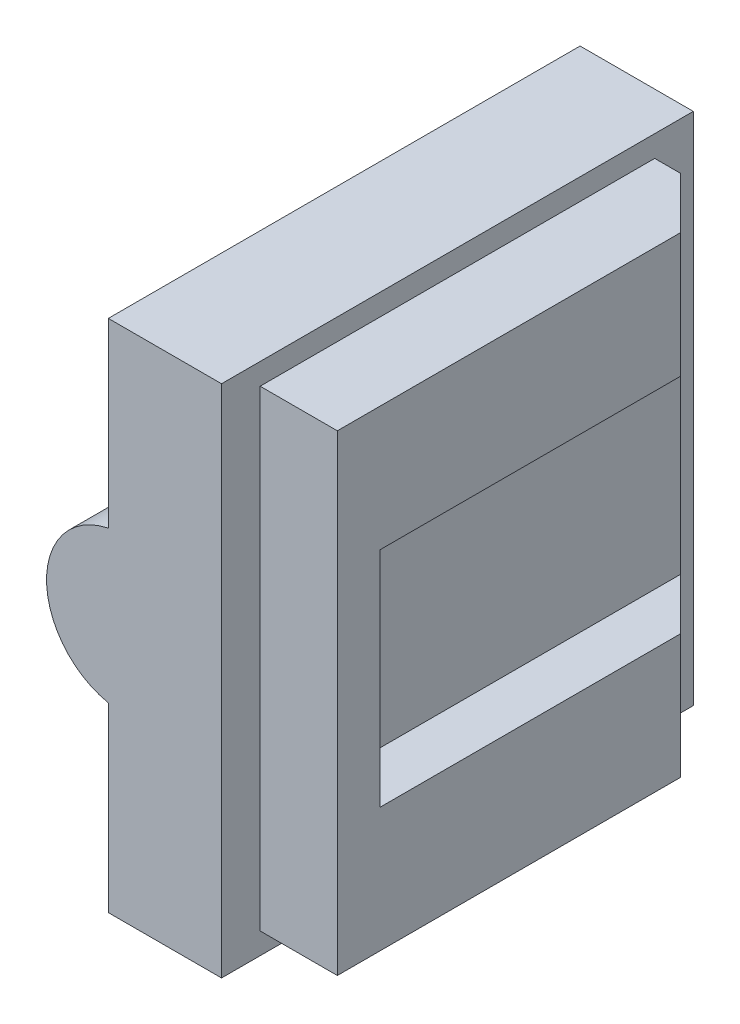
SolidWorks part; units mm, degrees
ref_plane "前视基准面" through (0, 0, 0) normal (0, 0, 1) x (1, 0, 0)
ref_plane "上视基准面" through (0, 0, 0) normal (0, 1, 0) x (1, 0, 0)
ref_plane "右视基准面" through (0, 0, 0) normal (1, 0, 0) x (0, 0, -1)
other "Configuration Table"
sketch "草图1" plane through (0, 0, 0) normal (0, 1, 0) x (1, 0, 0)
  line L0 (-0.3058, 8.6946) -> (9.8, 9.05)
  line L1 (9.8, 9.05) -> (9.8, -9.05)
  line L2 (9.8, -9.05) -> (-0.3058, -8.6946)
  line L3 (0, 0) -> (9.8, 0) construction
  circle A0 centre (0, 0) radius 2.9
  arc A1 (-0.3058, 8.6946) -> (-0.3058, -8.6946) centre (0, 0) ccw
  dimension "D1" = 5.8
  dimension "D4" = 17.4
  dimension "D2" = 9.8
  dimension "D3" = 18.1
extrude "凸台-拉伸1" add sketch "草图1" along normal blind 30
sketch "草图2" plane through (9.8, 0, 0) normal (1, 0, 0) x (0, 0, -1)
  line L0 (0, 30) -> (0, 0) construction
  line L1 (-13.75, 30) -> (13.75, 30)
  line L2 (-13.75, 30) -> (-13.75, 0)
  line L3 (-13.75, 0) -> (13.75, 0)
  line L4 (13.75, 30) -> (13.75, 0)
  line L5 (-9.05, 30) -> (9.05, 30) construction
  line L6 (-9.05, 0) -> (9.05, 0) construction
  dimension "D1" = 27.5
extrude "凸台-拉伸2" add sketch "草图2" along normal blind 17
sketch "草图3" plane through (9.8, 0, 0) normal (-1, 0, 0) x (0, 0, 1)
  line L0 (-13.75, 0) -> (-13.75, 30) construction
  line L1 (-13.75, 24.9) -> (13.75, 24.9)
  line L2 (-13.75, 24.9) -> (-13.75, 5.1)
  line L3 (-13.75, 5.1) -> (13.75, 5.1)
  line L4 (13.75, 24.9) -> (13.75, 5.1)
  line L5 (13.75, 30) -> (13.75, 0) construction
  line L6 (-13.75, 15) -> (13.75, 15) construction
  dimension "D1" = 19.8
extrude "切除-拉伸1" cut sketch "草图3" along normal up to next
sketch "草图4" plane through (26.8, 0, 0) normal (1, 0, 0) x (0, 0, -1)
  line L0 (0, 30) -> (0, 28.75) construction
  line L1 (-11.5, 28.75) -> (11.5, 28.75)
  line L2 (-11.5, 28.75) -> (-11.5, 1.25)
  line L3 (-11.5, 1.25) -> (11.5, 1.25)
  line L4 (-13.75, 30) -> (-13.75, 0)
  line L5 (-13.75, 0) -> (13.75, 0)
  line L6 (13.75, 0) -> (13.75, 30)
  line L7 (13.75, 30) -> (-13.75, 30)
  line L8 (-13.75, 30) -> (-13.75, 0)
  line L9 (-13.75, 0) -> (13.75, 0)
  line L10 (13.75, 0) -> (13.75, 30)
  line L11 (13.75, 30) -> (-13.75, 30)
  line L12 (11.5, 28.75) -> (11.5, 1.25)
  line L13 (-13.75, 15) -> (-11.5, 15) construction
  dimension "D2" = 27.5
  dimension "D3" = 23
  dimension "D1" = 0
extrude "切除-拉伸2" cut sketch "草图4" against normal blind 4.5
chamfer "倒角1" distance 3 angle 45 1 edges at (26.8, 15, -11.5)
sketch "草图5" plane through (26.8, 0, 0) normal (1, 0, 0) x (0, 0, -1)
  line L0 (11.5, 28.75) -> (11.5, 1.25) construction
  line L1 (11.5, 21.5) -> (-9, 21.5)
  line L2 (11.5, 21.5) -> (11.5, 8.5)
  line L3 (11.5, 8.5) -> (-9, 8.5)
  line L4 (-9, 21.5) -> (-9, 8.5)
  line L5 (-11.5, 15) -> (-9, 15) construction
  line L6 (-11.5, 28.75) -> (-11.5, 1.25) construction
  line L7 (-11.5, 28.75) -> (-11.5, 1.25) construction
  dimension "D1" = 13
  dimension "D2" = 2.5
extrude "切除-拉伸3" cut sketch "草图5" against normal blind 3
sketch "草图6" plane through (0, 30, 0) normal (0, 1, 0) x (1, 0, 0)
  circle A0 centre (0, 0) radius 2.9
  circle A1 centre (0, 0) radius 7.5
  circle A2 centre (0, 0) radius 2.9 construction
  dimension "D1" = 15
extrude "凸台-拉伸3" add sketch "草图6" along normal blind 2.2
chamfer "倒角2" distance 2 angle 45 1 edges at (0, 32.2, 7.5)
ref_plane "基准面1" through (0, 15, 0) normal (0, -1, 0) x (-1, 0, 0)
mirror "镜向1" about plane through (0, 15, 0) normal (0, -1, 0) of "凸台-拉伸3", "倒角2"
sketch "草图7" plane through (0, 0, -13.75) normal (0, 0, -1) x (-1, 0, 0)
  line L0 (5.5, 32.2) -> (-5.5, 32.2) construction
  line L1 (-15.7, 32.2) -> (9.3, 32.2)
  line L2 (-15.7, 32.2) -> (-15.7, -2.2)
  line L3 (-15.7, -2.2) -> (9.3, -2.2)
  line L4 (9.3, 32.2) -> (9.3, -2.2)
  line L5 (-5.5, -2.2) -> (5.5, -2.2) construction
  line L6 (-22.3, 0) -> (-22.3, 30) construction
  dimension "D1" = 6.6
  dimension "D2" = 25
extrude "切除-拉伸4" cut sketch "草图7" against normal up to next
sketch "草图8" plane through (15.7, 0, 0) normal (-1, 0, 0) x (0, 0, 1)
  line L0 (0, 30) -> (0, 0) construction
  line L1 (-12.625, 28.875) -> (12.625, 28.875)
  line L2 (-12.625, 28.875) -> (-12.625, 1.125)
  line L3 (-12.625, 1.125) -> (12.625, 1.125)
  line L4 (12.625, 28.875) -> (12.625, 1.125)
  line L5 (-12.425, 28.675) -> (12.425, 28.675)
  line L6 (-12.425, 28.675) -> (-12.425, 1.325)
  line L7 (-12.425, 1.325) -> (12.425, 1.325)
  line L8 (12.425, 28.675) -> (12.425, 1.325)
  line L9 (-13.75, 30) -> (13.75, 30) construction
  line L10 (-13.75, 0) -> (13.75, 0) construction
  line L11 (-13.75, 15) -> (13.75, 15) construction
  line L12 (-13.75, 30) -> (-13.75, 0) construction
  line L13 (13.75, 0) -> (13.75, 30) construction
  dimension "D1" = 27.75
  dimension "D2" = 25.25
  dimension "D3" = 0.2
  dimension "D4" = 0.2
extrude "凸台-拉伸4" add sketch "草图8" along normal blind 0.5
sketch "草图9" plane through (15.7, 0, 0) normal (-1, 0, 0) x (0, 0, 1)
  line L4 (12.425, 28.675) -> (-12.425, 28.675)
  line L5 (-12.425, 28.675) -> (-12.425, 1.325)
  line L6 (-12.425, 1.325) -> (12.425, 1.325)
  line L7 (12.425, 1.325) -> (12.425, 28.675)
  line L8 (12.425, 28.675) -> (-12.425, 28.675)
  line L9 (-12.425, 28.675) -> (-12.425, 1.325)
  line L10 (-12.425, 1.325) -> (12.425, 1.325)
  line L11 (12.425, 1.325) -> (12.425, 28.675)
  dimension "D1" = 0
extrude "切除-拉伸5" cut sketch "草图9" against normal blind 5
sketch "草图10" plane through (0, 0, 13.75) normal (0, 0, 1) x (1, 0, 0)
  line L0 (-55, 15) -> (55, 15) construction
  line L1 (15.7, 0) -> (15.7, 30) construction
  circle A0 centre (16.6, 15) radius 4.5
  point P4 (0, 0)
  dimension "D1" = 9
  dimension "D2" = 0.9
extrude "凸台-拉伸5" add sketch "草图10" against normal blind 5
sketch "草图11" plane through (15.7, 0, 0) normal (-1, 0, 0) x (0, 0, 1)
  line L0 (-13.75, 15) -> (10.5, 15) construction
  line L1 (-10.5, 26.5) -> (10.5, 26.5) construction
  line L2 (-10.5, 26.5) -> (-10.5, 3.5) construction
  line L3 (-10.5, 3.5) -> (10.5, 3.5) construction
  line L4 (10.5, 26.5) -> (10.5, 3.5) construction
  line L5 (-13.75, 30) -> (-13.75, 0) construction
  line L6 (0, 26.5) -> (0, 0) construction
  line L8 (-13.75, 0) -> (13.75, 0) construction
  circle A0 centre (-10.5, 26.5) radius 0.85
  circle A1 centre (10.5, 26.5) radius 0.85
  circle A2 centre (10.5, 3.5) radius 0.85
  circle A3 centre (-10.5, 3.5) radius 0.85
  circle A4 centre (-10.5, 26.5) radius 2.85
  circle A5 centre (10.5, 26.5) radius 2.85
  circle A6 centre (-10.5, 3.5) radius 2.85
  circle A7 centre (10.5, 3.5) radius 2.85
  dimension "D1" = 23
  dimension "D3" = 1.7
  dimension "D2" = 21
  dimension "D4" = 2
extrude "凸台-拉伸6" add sketch "草图11" against normal up to surface (5 mm away) up to face at (20.7, 15, 5.2937)
